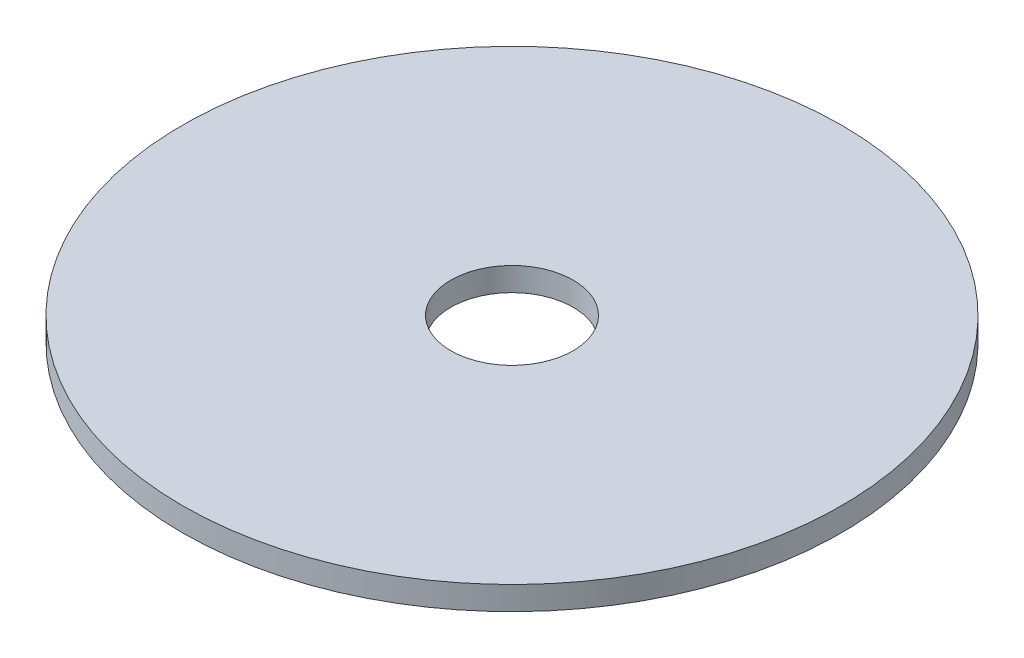
SolidWorks part; units mm, degrees
ref_plane "Ön Düzlem" through (0, 0, 0) normal (0, 0, 1) x (1, 0, 0)
ref_plane "Üst Düzlem" through (0, 0, 0) normal (0, 1, 0) x (1, 0, 0)
ref_plane "Sağ Düzlem" through (0, 0, 0) normal (1, 0, 0) x (0, 0, -1)
sketch "Çizim1" plane through (0, 0, 0) normal (0, 1, 0) x (1, 0, 0)
  circle A0 centre (0, 0) radius 140
extrude "Yükseklik-Ekstrüzyon1" add sketch "Çizim1" along normal blind 10
sketch "Çizim2" plane through (0, 10, 0) normal (0, 1, 0) x (1, 0, 0)
  circle A0 centre (0, 0) radius 26
extrude "Kes-Ekstrüzyon1" cut sketch "Çizim2" against normal blind 10
